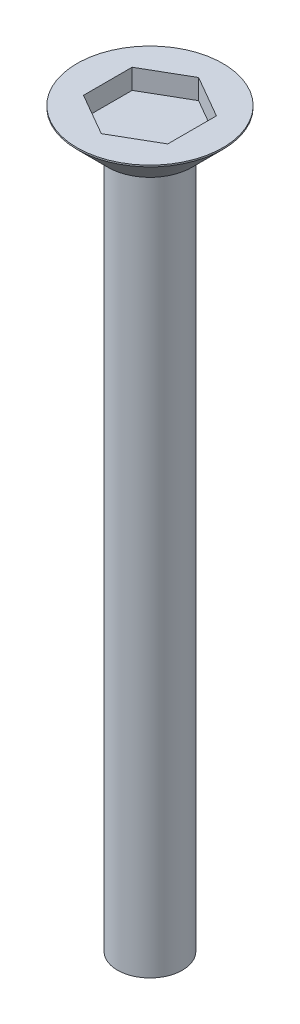
SolidWorks part; units mm, degrees
material "Cast Alloy Steel"
ref_plane "Front Plane" through (0, 0, 0) normal (0, 0, 1) x (1, 0, 0)
ref_plane "Top Plane" through (0, 0, 0) normal (0, 1, 0) x (1, 0, 0)
ref_plane "Right Plane" through (0, 0, 0) normal (1, 0, 0) x (0, 0, -1)
sketch "Sketch1" plane through (0, 0, 0) normal (0, 1, 0) x (1, 0, 0)
  circle A0 centre (0, 0) radius 2
  dimension "D1" = 4
extrude "Length" add sketch "Sketch1" along normal blind 43.18
sketch "Sketch2" plane through (0, 43.18, 0) normal (0, 1, 0) x (1, 0, 0)
  circle A0 centre (0, 0) radius 4.5
  dimension "D1" = 9
extrude "Cap" add sketch "Sketch2" along normal blind 2
sketch "Sketch3" plane through (0, 45.18, 0) normal (0, 1, 0) x (1, 0, 0)
  line L1 (0, 3) -> (-2.5981, 1.5)
  line L2 (-2.5981, 1.5) -> (-2.5981, -1.5)
  line L3 (-2.5981, -1.5) -> (0, -3)
  line L4 (0, -3) -> (2.5981, -1.5)
  line L5 (2.5981, -1.5) -> (2.5981, 1.5)
  line L6 (2.5981, 1.5) -> (0, 3)
  circle A0 centre (0, 0) radius 2.5981 construction
  point P1 (0, 0)
  dimension "D1" = 3
extrude "Hex cut" cut sketch "Sketch3" against normal blind 1.238
chamfer "Chamfer1" distance 1.905 angle 45 1 edges at (0, 43.18, 4.5)
